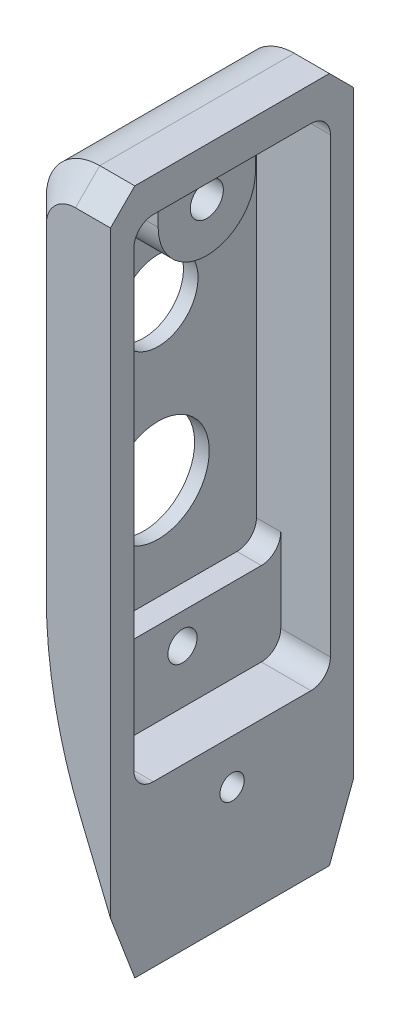
SolidWorks part; units mm, degrees
material "Сплав 2024"
ref_plane "Спереди" through (0, 0, 0) normal (0, 0, 1) x (1, 0, 0)
ref_plane "Сверху" through (0, 0, 0) normal (0, 1, 0) x (1, 0, 0)
ref_plane "Справа" through (0, 0, 0) normal (1, 0, 0) x (0, 0, -1)
sketch "Эскиз1" plane through (0, 0, 0) normal (0, 0, 1) x (1, 0, 0)
  line L0 (0, 0) -> (0, 70.5)
  line L1 (-3.6, 70.5) -> (0, 70.5)
  line L2 (-9.1, 65) -> (-9.1, 32)
  line L3 (-5.3384, 12.9735) -> (0, 0)
  arc A0 (-3.6, 70.5) -> (-9.1, 65) centre (-3.6, 65) ccw
  arc A1 (-9.1, 32) -> (-5.3384, 12.9735) centre (40.9, 32) ccw
  dimension "D2" = 50
  dimension "D5" = 32
  dimension "D1" = 9.1
  dimension "D3" = 70.5
  dimension "D4" = 33
  dimension "D6" = 5.5
extrude "Бобышка-Вытянуть1" add sketch "Эскиз1" along normal blind 25
chamfer "Фаска5" distance 2.5 angle 45 10 edges at (-1.8, 70.5, 0) (-1.8, 70.5, 25) (-2.6692, 6.4867, 0) (-2.6692, 6.4867, 25) (-7.4891, 68.8891, 0) (-7.4891, 68.8891, 25) (-8.1506, 22.3026, 0) (-8.1506, 22.3026, 25) (-9.1, 48.5, 0) (-9.1, 48.5, 25)
sketch "Эскиз6" plane through (0, 0, 0) normal (1, 0, 0) x (0, 0, -1)
  line L0 (-12.5, 70.5) -> (-12.5, 0) construction
  line L1 (-22.5, 70.5) -> (-2.5, 70.5) construction
  line L2 (-22.5, 0) -> (-2.5, 0) construction
  line L4 (-22.6, 67) -> (-2.4, 67)
  line L5 (-22.6, 67) -> (-22.6, 25.1087)
  line L6 (-22.6, 25.1087) -> (-2.4, 25.1087)
  line L7 (-2.4, 67) -> (-2.4, 25.1087)
  line L8 (-22.6, 67) -> (-2.4, 25.1087) construction
  line L9 (-22.6, 25.1087) -> (-2.4, 67) construction
  point P6 (-12.5, 46.0543)
  dimension "D1" = 20.2
  dimension "D2" = 3.5
  dimension "D3" = 25.1087
extrude "Вырез-Вытянуть2" cut sketch "Эскиз6" against normal offset from surface (7.6 mm away) 1.5 up to face at (-9.1, 48.5, 12.5)
sketch "Эскиз7" plane through (-9.1, 0, 0) normal (-1, 0, 0) x (0, 0, 1)
  line L0 (12.5, 65) -> (12.5, 25.4737) construction
  line L1 (22.5, 65) -> (2.5, 65) construction
  line L3 (22.5, 0) -> (2.5, 0) construction
  circle A0 centre (12.5, 35.5) radius 5.25
  circle A1 centre (12.5, 51.5) radius 4.1
  dimension "D1" = 10.5
  dimension "D2" = 8.2
  dimension "D3" = 35.5
  dimension "D4" = 16
extrude "Вырез-Вытянуть3" cut sketch "Эскиз7" against normal through all
ref_plane "Плоскость1" through (0, 0, 12.5) normal (0, 0, 1) x (1, 0, 0)
sketch "Эскиз8" plane through (0, 0, 0) normal (1, 0, 0) x (0, 0, -1)
  line L1 (-22.6, 25.1087) -> (-2.4, 25.1087)
  line L2 (-22.6, 25.1087) -> (-22.6, 16.5228)
  line L3 (-22.6, 16.5228) -> (-2.4, 16.5228)
  line L4 (-2.4, 25.1087) -> (-2.4, 16.5228)
extrude "Вырез-Вытянуть4" cut sketch "Эскиз8" against normal offset from surface (5.1 mm away) 2.5 up to face at (-7.6, 55.6, 12.5)
fillet "Скругление2" radius 2 6 edges at (-2.55, 16.5228, 2.4) (-2.55, 16.5228, 22.6) (-6.35, 25.1087, 22.6) (-6.35, 25.1087, 2.4) (-3.8, 67, 2.4) (-3.8, 67, 22.6)
sketch "Эскиз10" plane through (-9.1, 0, 0) normal (-1, 0, 0) x (0, 0, 1)
  line L0 (12.5, 35.5) -> (12.5, 15.9746) construction
  circle A0 centre (12.5, 22) radius 1.5
  dimension "D1" = 3
  dimension "D2" = 13.5
extrude "Вырез-Вытянуть5" cut sketch "Эскиз10" against normal up to next
sketch "Эскиз11" plane through (0, 0, 0) normal (1, 0, 0) x (0, 0, -1)
  line L0 (-12.5, 16.5228) -> (-12.5, 3.5837) construction
  line L1 (-4.4, 16.5228) -> (-20.6, 16.5228) construction
  line L2 (-22.5, 70.5) -> (-2.5, 70.5) construction
  point P4 (-12.5, 12)
  point P5 (-12.5, 70.5)
  dimension "D1" = 58.5
hole_wizard "Отверстие обработанное метчиком M3x0.51" positions "Эскиз13" profile "Эскиз12" tap size "M3x0.5" standard "Ansi Metric"
sketch "Эскиз13" plane through (0, 0, 0) normal (1, 0, 0) x (0, 0, -1)
  point P0 (-12.5, 12)
sketch "Эскиз12" plane through (0, 12, 12.5) normal (0, 1, 0) x (0, 0, -1)
  line L0 (0, 0) -> (0, 3.7511)
  line L1 (0, 3.7511) -> (1.25, 3)
  line L2 (1.25, 3) -> (1.25, 0)
  line L5 (1.25, 0) -> (0, 0)
  line L10 (0, 3.7511) -> (-1.25, 3) construction
  line L11 (0, -6.35) -> (0, 107.95) construction
  dimension "Диаметр сверла" = 2.5
  dimension "Глубина сверла" = 3
  dimension "Угол заточки сверла" = 118
cosmetic thread "Отверстие резьбы1" parameters "D1"=3, "D2"=3
sketch "Эскиз15" plane through (0, 0, 0) normal (1, 0, 0) x (0, 0, -1)
  line L0 (-12.5, 70.5) -> (-12.5, 67) construction
  line L1 (-22.5, 70.5) -> (-2.5, 70.5) construction
  line L2 (-4.4, 67) -> (-20.6, 67) construction
  point P6 (-12.5, 65.5)
  dimension "D1" = 5
sketch "Эскиз18" plane through (-9.1, 0, 0) normal (-1, 0, 0) x (0, 0, 1)
  line L0 (12.5, 65) -> (12.5, 72.0513) construction
  line L1 (22.5, 65) -> (2.5, 65) construction
  line L2 (22.5, 70.5) -> (2.5, 70.5) construction
  point P4 (12.5, 68)
  dimension "D1" = 2.5
sketch "Эскиз22" plane through (-7.6, 0, 0) normal (1, 0, 0) x (0, 0, -1)
  line L1 (-12.5, 67) -> (-12.5, 58.1189) construction
  line L2 (-20.6, 67) -> (-4.4, 67) construction
  line L3 (-17.5, 63) -> (-17.5, 67)
  line L4 (-4.4, 67) -> (-20.6, 67) construction
  line L5 (-17.5, 67) -> (-7.5, 67)
  line L6 (-7.5, 67) -> (-7.5, 63)
  arc A0 (-17.5, 63) -> (-7.5, 63) centre (-12.5, 63) ccw
  dimension "D1" = 10
  dimension "D2" = 4
extrude "Бобышка-Вытянуть3" add sketch "Эскиз22" along normal blind 5
fillet "Скругление3" radius 2 2 edges at (-5.1, 67, 7.5) (-5.1, 67, 17.5)
hole_wizard "Цековка для винта с внутренним шестигранником M32" positions "Эскиз24" profile "Эскиз23" counterbore size "M3" standard "Ansi Metric" end condition through all
sketch "Эскиз24" plane through (-9.1, 0, 0) normal (-1, 0, 0) x (0, 0, 1)
  point P0 (12.5, 63)
sketch "Эскиз23" plane through (-9.1, 63, 12.5) normal (0, 1, 0) x (0, 0, 1)
  line L0 (0, 0) -> (0, 9.1)
  line L1 (0, 9.1) -> (1.7, 9.1)
  line L3 (1.7, 9.1) -> (1.7, 2.5)
  line L4 (1.7, 2.5) -> (3.25, 2.5)
  line L5 (3.25, 2.5) -> (3.25, 0)
  line L7 (3.25, 0) -> (0, 0)
  line L11 (0, -6.35) -> (0, 107.95) construction
  dimension "Диаметр сквозного отверстия" = 3.4
  dimension "Глубина сквозного отверстия" = 9.1
  dimension "Диаметр цековки" = 6.5
  dimension "Глубина цековки" = 2.5
sketch "Эскиз25" [suppressed] plane through (0, 0, 25) normal (0, 0, 1) x (1, 0, 0)
  line L1 (0, 70.5) -> (-8.7273, 70.5)
  line L2 (0, 70.5) -> (0, 74.5223)
  line L3 (0, 74.5223) -> (-8.7273, 74.5223)
  line L4 (-8.7273, 70.5) -> (-8.7273, 74.5223)
extrude "Вырез-Вытянуть6" [suppressed] cut sketch "Эскиз25" against normal up to next
equation "\"D3@Эскиз1\"=73.00-2.5"
equation "\"D1@Эскиз1\"=8.50+0.6"
